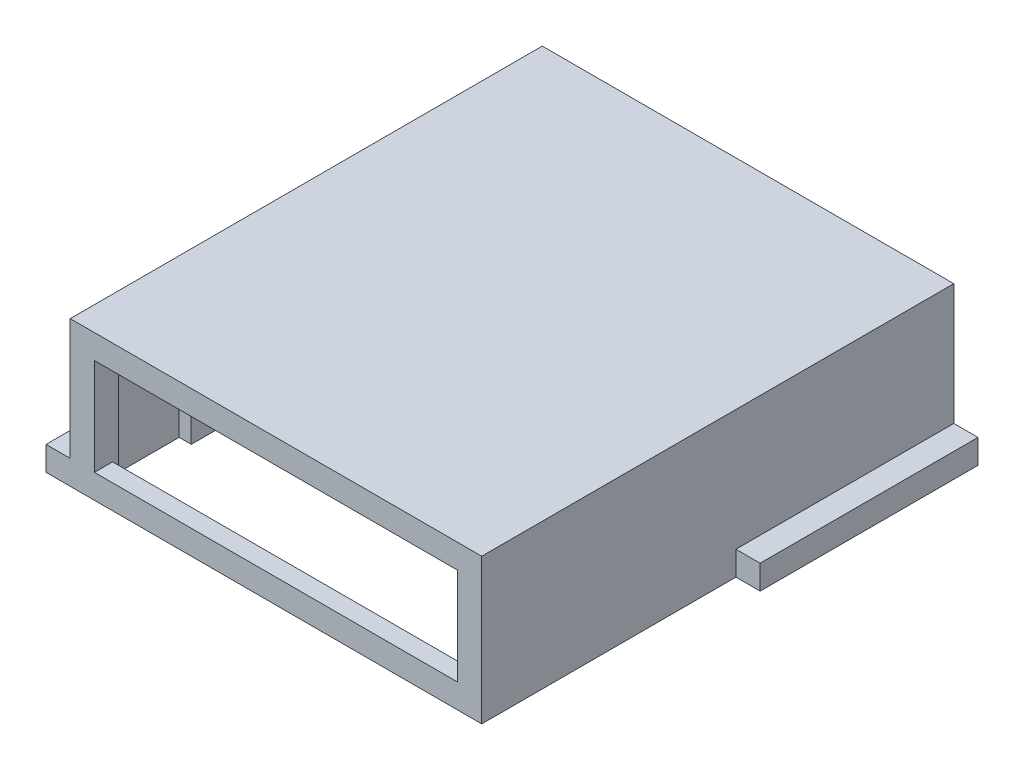
SolidWorks part; units mm, degrees
ref_plane "Front Plane" through (0, 0, 0) normal (0, 0, 1) x (1, 0, 0)
ref_plane "Top Plane" through (0, 0, 0) normal (0, 1, 0) x (1, 0, 0)
ref_plane "Right Plane" through (0, 0, 0) normal (1, 0, 0) x (0, 0, -1)
sketch "Sketch1" plane through (0, 0, 0) normal (0, 1, 0) x (1, 0, 0)
  line L1 (-5.6818, 8.1818) -> (11.3182, 8.1818)
  line L2 (-5.6818, 8.1818) -> (-5.6818, -11.3182)
  line L3 (-5.6818, -11.3182) -> (11.3182, -11.3182)
  line L4 (11.3182, 8.1818) -> (11.3182, -11.3182)
  dimension "D1" = 17
  dimension "D2" = 19.5
extrude "Boss-Extrude1" add sketch "Sketch1" along normal blind 6
sketch "Sketch2" plane through (0, 0, 0) normal (0, 1, 0) x (1, 0, 0)
  line L0 (-5.6818, -1.5682) -> (11.3182, -1.5682) construction
  line L1 (-5.6818, 8.1818) -> (-5.6818, -11.3182) construction
  line L2 (11.3182, -11.3182) -> (11.3182, 8.1818) construction
  line L3 (2.8182, 8.1818) -> (2.8182, -11.3182) construction
  line L4 (11.3182, 8.1818) -> (-5.6818, 8.1818) construction
  line L5 (-5.6818, -11.3182) -> (11.3182, -11.3182) construction
  line L7 (-4.6818, 7.4318) -> (10.3182, 7.4318)
  line L8 (-4.6818, 7.4318) -> (-4.6818, -10.5682)
  line L9 (-4.6818, -10.5682) -> (10.3182, -10.5682)
  line L10 (10.3182, 7.4318) -> (10.3182, -10.5682)
  line L11 (-4.6818, 7.4318) -> (10.3182, -10.5682) construction
  line L12 (-4.6818, -10.5682) -> (10.3182, 7.4318) construction
  point P12 (2.8182, -1.5682)
  dimension "D1" = 15
  dimension "D2" = 18
extrude "Cut-Extrude1" cut sketch "Sketch2" along normal blind 5.2
sketch "Sketch3" plane through (-5.6818, 0, 0) normal (-1, 0, 0) x (0, 0, 1)
  line L0 (11.3182, 6) -> (11.3182, 0) construction
  line L1 (2.3182, 0) -> (11.3182, 0)
  line L2 (2.3182, 0) -> (2.3182, 1)
  line L3 (2.3182, 1) -> (11.3182, 1)
  line L4 (11.3182, 0) -> (11.3182, 1)
  dimension "D1" = 1
  dimension "D2" = 9
sketch "Sketch4" plane through (11.3182, 0, 0) normal (1, 0, 0) x (0, 0, -1)
  line L0 (-11.3182, 0) -> (8.1818, 0) construction
  line L1 (-0.8182, 0) -> (8.1818, 0)
  line L2 (-0.8182, 0) -> (-0.8182, 1)
  line L3 (-0.8182, 1) -> (8.1818, 1)
  line L4 (8.1818, 0) -> (8.1818, 1)
  line L5 (8.1818, 6) -> (8.1818, 0) construction
  dimension "D1" = 9
  dimension "D2" = 1
extrude "Boss-Extrude2" add sketch "Sketch4" along normal blind 1
extrude "Boss-Extrude3" add sketch "Sketch3" along normal blind 1
sketch "Sketch5" plane through (0, 0, 11.3182) normal (0, 0, 1) x (1, 0, 0)
  line L0 (2.8182, 3) -> (2.8182, 6) construction
  line L1 (-4.6818, 1) -> (10.3182, 1)
  line L2 (-4.6818, 1) -> (-4.6818, 5)
  line L3 (-4.6818, 5) -> (10.3182, 5)
  line L4 (10.3182, 1) -> (10.3182, 5)
  line L5 (-4.6818, 1) -> (10.3182, 5) construction
  line L6 (-4.6818, 5) -> (10.3182, 1) construction
  line L7 (-5.6818, 6) -> (11.3182, 6) construction
  point P6 (2.8182, 3)
  point P8 (2.8182, 6)
  dimension "D1" = 15
  dimension "D2" = 4
  dimension "D3" = 1
extrude "Cut-Extrude2" cut sketch "Sketch5" against normal blind 14
sketch "Sketch6" plane through (0, 0, 0) normal (0, 1, 0) x (1, 0, 0)
  line L0 (10.3182, 7.4318) -> (-4.6818, 7.4318) construction
  line L1 (-5.1818, 7.4318) -> (10.8182, 7.4318)
  line L2 (-5.1818, 7.4318) -> (-5.1818, 3.4318)
  line L3 (-5.1818, 3.4318) -> (10.8182, 3.4318)
  line L4 (10.8182, 7.4318) -> (10.8182, 3.4318)
  line L5 (-4.6818, -11.3182) -> (10.3182, -11.3182) construction
  line L6 (-5.1818, -10.3182) -> (10.8182, -10.3182)
  line L7 (-5.1818, -10.3182) -> (-5.1818, -7.3182)
  line L8 (-5.1818, -7.3182) -> (10.8182, -7.3182)
  line L9 (10.8182, -10.3182) -> (10.8182, -7.3182)
  line L10 (10.3182, -11.3182) -> (-4.6818, -11.3182) construction
  line L11 (11.3182, -11.3182) -> (11.3182, -0.8182) construction
  line L13 (-6.6818, -11.3182) -> (11.3182, -11.3182) construction
  point P10 (2.8182, 7.4318)
  point P16 (0, 0)
  dimension "D1" = 16
  dimension "D2" = 16
  dimension "D3" = 3
  dimension "D4" = 4
  dimension "D5" = 0.5
  dimension "D6" = 1
extrude "Cut-Extrude3" cut sketch "Sketch6" along normal blind 4
